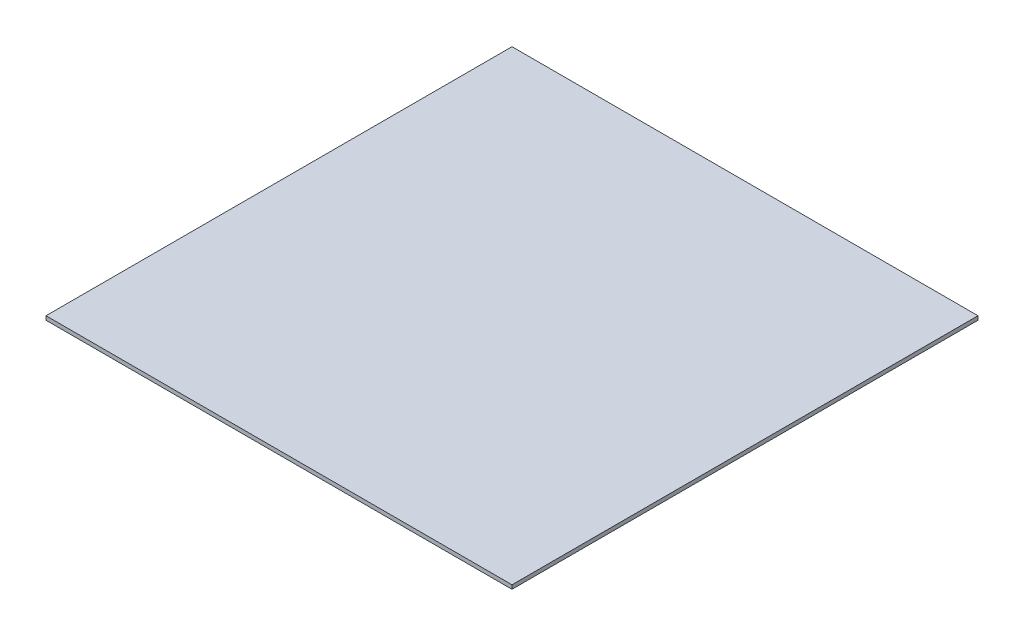
SolidWorks part; units mm, degrees
ref_plane "Front Plane" through (0, 0, 0) normal (0, 0, 1) x (1, 0, 0)
ref_plane "Top Plane" through (0, 0, 0) normal (0, 1, 0) x (1, 0, 0)
ref_plane "Right Plane" through (0, 0, 0) normal (1, 0, 0) x (0, 0, -1)
sketch "Sketch1" plane through (0, 0, 0) normal (0, 1, 0) x (1, 0, 0)
  line L5 (-94.8, -94.8) -> (94.8, -94.8)
  line L6 (-94.8, -94.8) -> (-94.8, 94.8)
  line L7 (-94.8, 94.8) -> (94.8, 94.8)
  line L8 (94.8, -94.8) -> (94.8, 94.8)
  line L9 (-94.8, -94.8) -> (94.8, 94.8) construction
  line L10 (-94.8, 94.8) -> (94.8, -94.8) construction
  point P0 (0, 0)
  dimension "D1" = 189.6
extrude "Boss-Extrude1" add sketch "Sketch1" along normal mid plane 1.6
